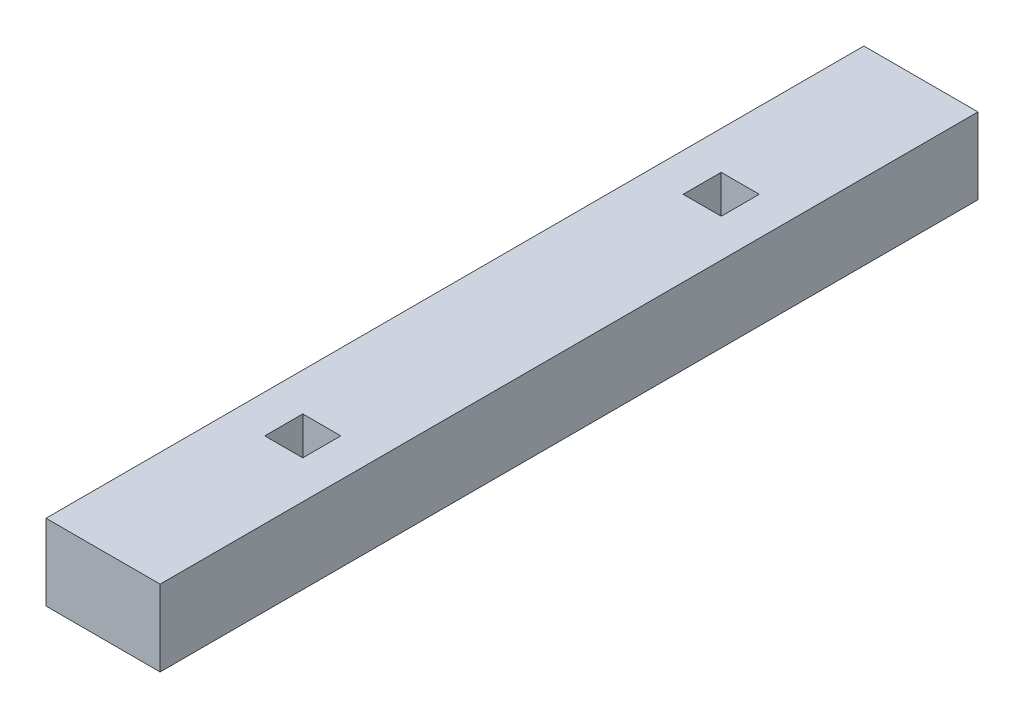
SolidWorks part; units mm, degrees
ref_plane "Front Plane" through (0, 0, 0) normal (0, 0, 1) x (1, 0, 0)
ref_plane "Top Plane" through (0, 0, 0) normal (0, 1, 0) x (1, 0, 0)
ref_plane "Right Plane" through (0, 0, 0) normal (1, 0, 0) x (0, 0, -1)
sketch "Sketch1" plane through (0, 0, 0) normal (0, 1, 0) x (1, 0, 0)
  line L0 (0, 102.5) -> (0, -112.5) construction
  line L1 (-15, 102.5) -> (15, 102.5)
  line L2 (-15, 102.5) -> (-15, -112.5)
  line L3 (-15, -112.5) -> (15, -112.5)
  line L4 (15, 102.5) -> (15, -112.5)
  line L5 (-5, 55) -> (5, 55)
  line L6 (-5, 55) -> (-5, 45)
  line L7 (-5, 45) -> (5, 45)
  line L8 (5, 55) -> (5, 45)
  line L9 (15, -5) -> (-15, -5) construction
  line L10 (-5, -65) -> (-5, -55)
  line L11 (-5, -55) -> (5, -55)
  line L12 (5, -65) -> (5, -55)
  line L13 (-5, -65) -> (5, -65)
  point P9 (0, 55)
  point P10 (0, 102.5)
  dimension "D3" = 10
  dimension "D5" = 100
  dimension "D4" = 10
  dimension "D1" = 30
  dimension "D2" = 215
extrude "Boss-Extrude1" add sketch "Sketch1" along normal blind 20
